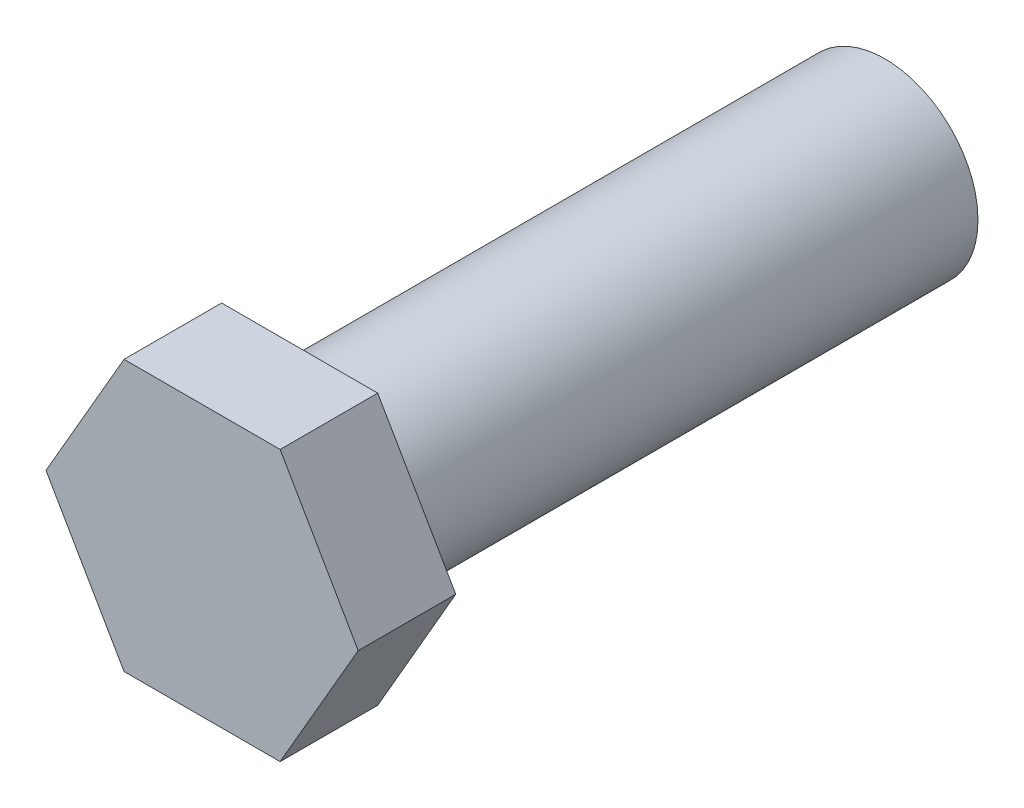
SolidWorks part; units mm, degrees
ref_plane "Plano frontal" through (0, 0, 0) normal (0, 0, 1) x (1, 0, 0)
ref_plane "Plano superior" through (0, 0, 0) normal (0, 1, 0) x (1, 0, 0)
ref_plane "Plano direito" through (0, 0, 0) normal (1, 0, 0) x (0, 0, -1)
sketch "Esboço1" plane through (0, 0, 0) normal (0, 0, 1) x (1, 0, 0)
  line L1 (8, 0) -> (4, 6.9282)
  line L2 (4, 6.9282) -> (-4, 6.9282)
  line L3 (-4, 6.9282) -> (-8, 0)
  line L4 (-8, 0) -> (-4, -6.9282)
  line L5 (-4, -6.9282) -> (4, -6.9282)
  line L6 (4, -6.9282) -> (8, 0)
  circle A0 centre (0, 0) radius 6.9282 construction
  dimension "D1" = 16
extrude "Ressalto-extrusão1" add sketch "Esboço1" along normal blind 5
sketch "Esboço2" plane through (0, 0, 0) normal (0, 0, -1) x (-1, 0, 0)
  circle A0 centre (0, 0) radius 4.765
  dimension "D1" = 9.53
extrude "Ressalto-extrusão2" add sketch "Esboço2" along normal blind 30
